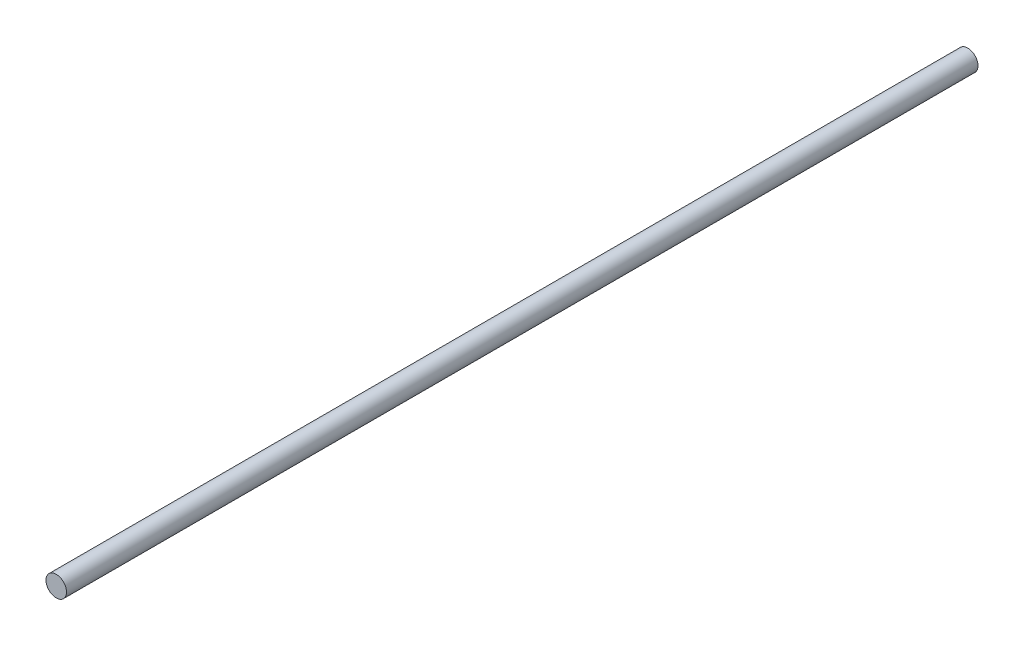
SolidWorks part; units mm, degrees
ref_plane "Front Plane" through (0, 0, 0) normal (0, 0, 1) x (1, 0, 0)
ref_plane "Top Plane" through (0, 0, 0) normal (0, 1, 0) x (1, 0, 0)
ref_plane "Right Plane" through (0, 0, 0) normal (1, 0, 0) x (0, 0, -1)
sketch "Sketch1" plane through (0, 0, 0) normal (0, 0, 1) x (1, 0, 0)
  circle A1 centre (0, 0) radius 0.3937
extrude "Boss-Extrude4" add sketch "Sketch1" along normal blind 35
